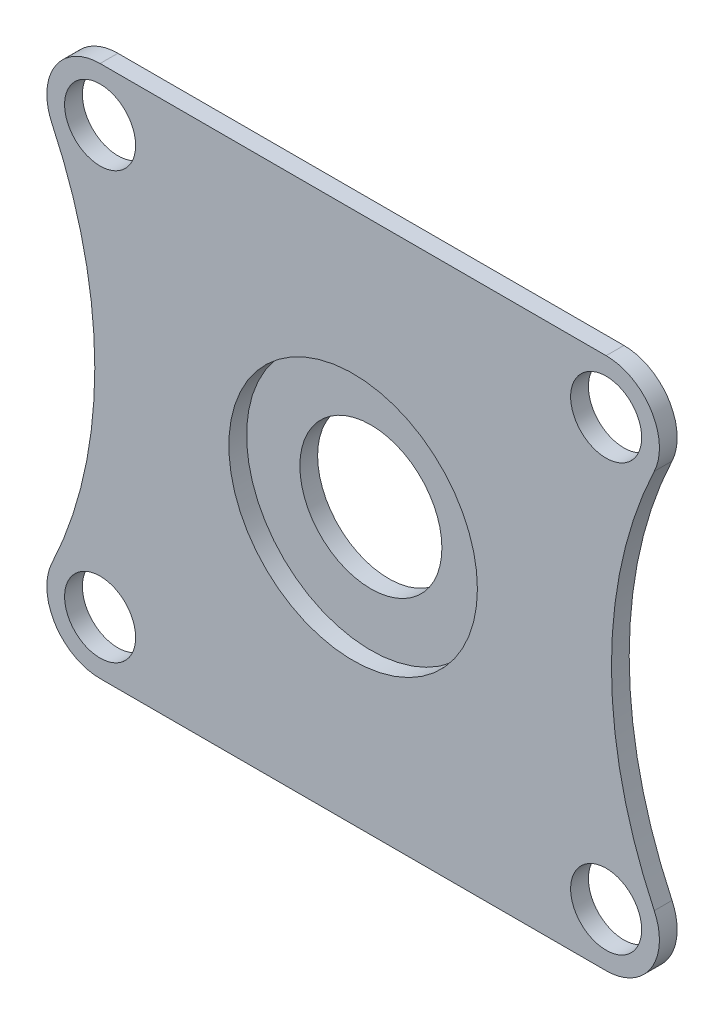
SolidWorks part; units mm, degrees
ref_plane "前视基准面" through (0, 0, 0) normal (0, 0, 1) x (1, 0, 0)
ref_plane "上视基准面" through (0, 0, 0) normal (0, 1, 0) x (1, 0, 0)
ref_plane "右视基准面" through (0, 0, 0) normal (1, 0, 0) x (0, 0, -1)
sketch "草图1" plane through (0, 0, 0) normal (0, 0, 1) x (1, 0, 0)
  line L0 (0, 0) -> (5.388, 0) construction
  line L1 (5.388, 0) -> (0, 0) construction
  line L2 (0, 0) -> (0, 6.4733) construction
  line L3 (-14.25, 12) -> (14.25, 12) construction
  line L4 (14.25, 12) -> (14.25, -12) construction
  line L5 (14.25, -12) -> (-14.25, -12) construction
  line L6 (-14.25, -12) -> (-14.25, 12) construction
  line L8 (-14.25, -15) -> (14.25, -15)
  line L9 (-14.25, 15) -> (14.25, 15)
  circle A0 centre (-14.25, 12) radius 2
  circle A1 centre (14.25, 12) radius 2
  circle A2 centre (14.25, -12) radius 2
  circle A3 centre (-14.25, -12) radius 2
  circle A4 centre (-14.25, 12) radius 3
  circle A5 centre (14.25, 12) radius 3
  circle A6 centre (14.25, -12) radius 3
  circle A7 centre (-14.25, -12) radius 3
  arc A8 (-16.9605, -10.7143) -> (-16.9605, 10.7143) centre (-39.5482, 0) ccw
  arc A9 (16.9605, -10.7143) -> (16.9605, 10.7143) centre (39.5482, 0) cw
  point P11 (0, 12)
  point P12 (14.25, 0)
  dimension "D3" = 4
  dimension "D4" = 4
  dimension "D5" = 6
  dimension "D6" = 50
  dimension "D1" = 28.5
  dimension "D2" = 24
sketch "草图2" plane through (0, 0, 0) normal (0, 0, 1) x (1, 0, 0)
  line L0 (-14.25, 15) -> (14.25, 15) construction
  line L1 (-14.25, -15) -> (14.25, -15) construction
  line L2 (-14.25, 15) -> (14.25, 15)
  line L3 (-14.25, -15) -> (14.25, -15)
  arc A0 (16.9605, 10.7143) -> (16.9605, -10.7143) centre (39.5482, 0) ccw construction
  circle A1 centre (14.25, 12) radius 2
  circle A2 centre (14.25, 12) radius 2
  circle A3 centre (-14.25, 12) radius 2
  circle A4 centre (-14.25, 12) radius 2
  circle A5 centre (-14.25, -12) radius 3
  arc A6 (-16.9605, -10.7143) -> (-14.25, -15) centre (-14.25, -12) ccw
  circle A7 centre (14.25, -12) radius 3
  arc A8 (14.25, -15) -> (16.9605, -10.7143) centre (14.25, -12) ccw
  circle A9 centre (14.25, 12) radius 3
  arc A10 (16.9605, 10.7143) -> (14.25, 15) centre (14.25, 12) ccw
  circle A11 centre (-14.25, 12) radius 3
  arc A12 (-14.25, 15) -> (-16.9605, 10.7143) centre (-14.25, 12) ccw
  circle A13 centre (-14.25, -12) radius 2
  circle A14 centre (-14.25, -12) radius 2
  circle A15 centre (14.25, -12) radius 2
  circle A16 centre (14.25, -12) radius 2
  arc A17 (-16.9605, -10.7143) -> (-16.9605, 10.7143) centre (-39.5482, 0) ccw construction
  arc A18 (16.9605, 10.7143) -> (16.9605, -10.7143) centre (39.5482, 0) ccw
  arc A19 (-16.9605, -10.7143) -> (-16.9605, 10.7143) centre (-39.5482, 0) ccw
  dimension "D1" = 0
  dimension "D2" = 0
  dimension "D3" = 0
  dimension "D4" = 0
  dimension "D5" = 0
  dimension "D6" = 0
  dimension "D7" = 0
  dimension "D8" = 0
extrude "凸台-拉伸1" add sketch "草图2" along normal blind 1
sketch "草图3" plane through (0, 0, 0) normal (0, 1, 0) x (1, 0, 0)
  line L0 (0, 0) -> (0, -2.4338) construction
  line L1 (0, 1) -> (8, 1)
  line L2 (8, 1) -> (12, 0)
  line L3 (-200000, 0) -> (200005.388, 0) construction
  line L4 (0, 0) -> (12, 0)
  line L5 (0, 1) -> (0, 0)
  dimension "D1" = 8
  dimension "D2" = 12
  dimension "D3" = 1
revolve "旋转1" add sketch "草图3" angle 360 about L0
fillet "圆角1" radius 10 1 edges at (-12, 0, 0)
fillet "圆角2" radius 10 1 edges at (-8, 0, -1)
sketch "草图4" plane through (0, 0, -1) normal (0, 0, -1) x (-1, 0, 0)
  circle A0 centre (0, 0) radius 4
  dimension "D1" = 8
extrude "切除-拉伸1" cut sketch "草图4" against normal blind 10
sketch "草图5" plane through (0, 0, 1) normal (0, 0, 1) x (1, 0, 0)
  circle A0 centre (0, 0) radius 7
  dimension "D1" = 14
extrude "切除-拉伸2" cut sketch "草图5" against normal blind 1
